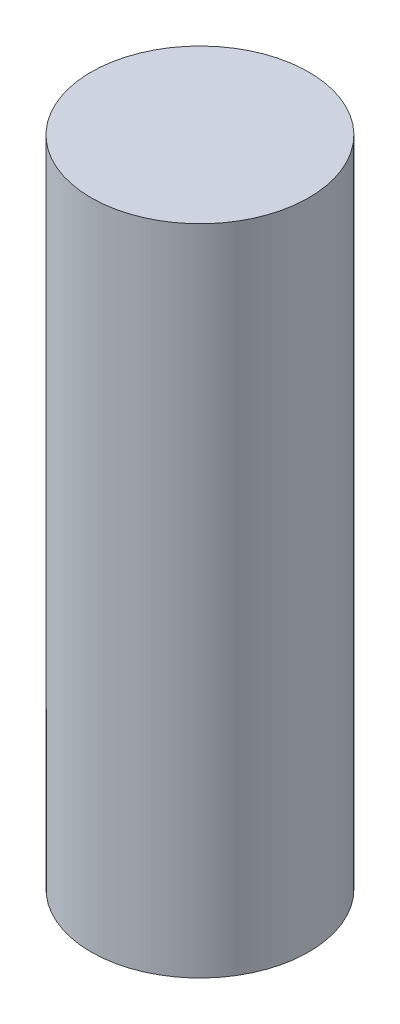
SolidWorks part; units mm, degrees
material "MS PLATE GRADE 350"
ref_plane "Section" through (0, 0, 0) normal (0, 0, 1) x (1, 0, 0)
ref_plane "Top Plane" through (0, 0, 0) normal (0, 1, 0) x (1, 0, 0)
ref_plane "Long" through (0, 0, 0) normal (1, 0, 0) x (0, 0, -1)
sketch "Sketch1" plane through (0, 0, 0) normal (0, 1, 0) x (1, 0, 0)
  circle A0 centre (0, 0) radius 25
  dimension "D1" = 50
extrude "Boss-Extrude1" add sketch "Sketch1" along normal blind 150
